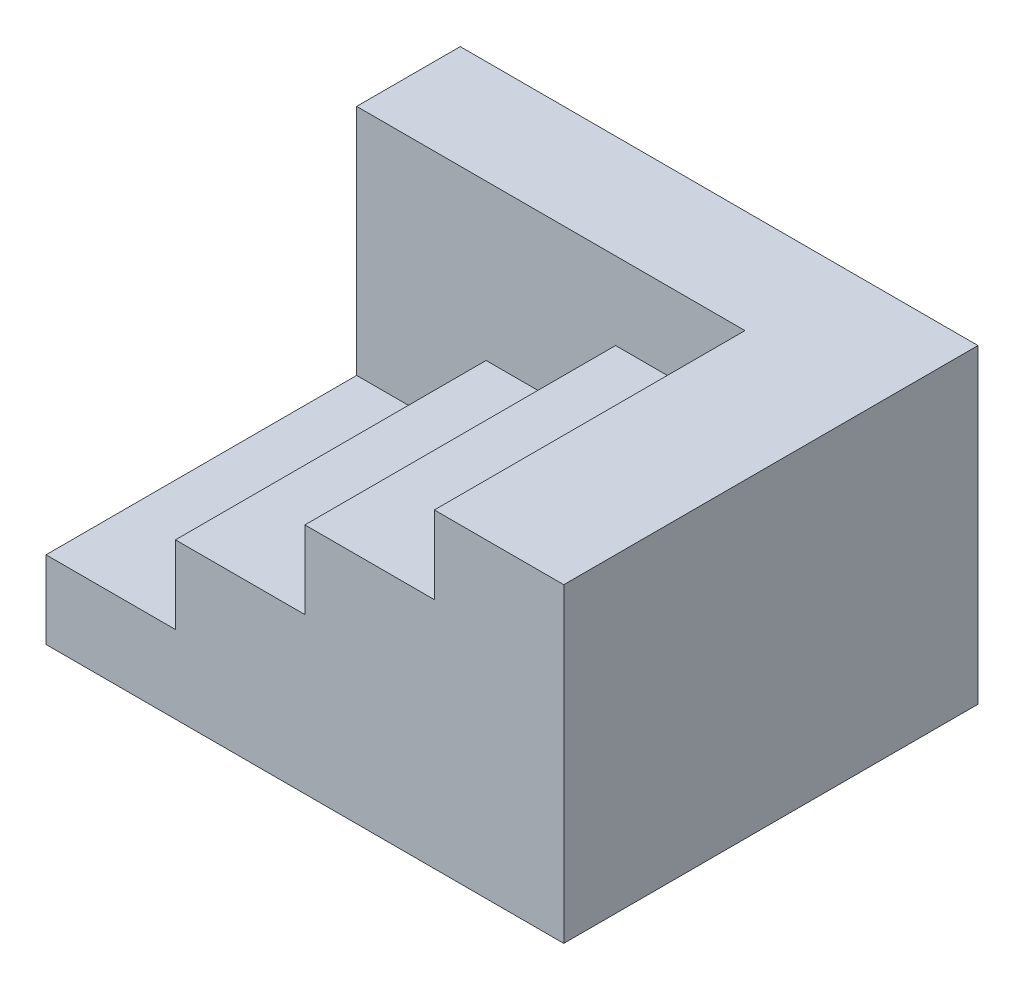
SolidWorks part; units mm, degrees
ref_plane "Front Plane" through (0, 0, 0) normal (0, 0, 1) x (1, 0, 0)
ref_plane "Top Plane" through (0, 0, 0) normal (0, 1, 0) x (1, 0, 0)
ref_plane "Right Plane" through (0, 0, 0) normal (1, 0, 0) x (0, 0, -1)
sketch "Sketch1" plane through (0, 0, 0) normal (0, 1, 0) x (1, 0, 0)
  line L1 (-50, -40) -> (50, -40)
  line L2 (-50, -40) -> (-50, 40)
  line L3 (-50, 40) -> (50, 40)
  line L4 (50, -40) -> (50, 40)
  point P0 (0, 0)
  dimension "D1" = 100
  dimension "D2" = 80
  dimension "D3" = 40
  dimension "D4" = 50
extrude "Boss-Extrude2" add sketch "Sketch1" along normal blind 60 contours L1 L4 L3 L2
sketch "Sketch3" plane through (0, 0, 40) normal (0, 0, 1) x (1, 0, 0)
  line L11 (50, 60) -> (25, 60)
  line L12 (25, 60) -> (25, 45)
  line L13 (25, 45) -> (0, 45)
  line L14 (0, 45) -> (0, 30)
  line L15 (-50, 0) -> (50, 0)
  line L16 (50, 0) -> (50, 60)
  line L17 (50, 60) -> (-50, 60)
  line L18 (-50, 60) -> (-50, 0)
  line L21 (50, 60) -> (-50, 60)
  line L23 (0, 30) -> (-25, 30)
  line L24 (-25, 30) -> (-25, 15)
  line L25 (-25, 15) -> (-50, 15)
  line L26 (-50, 60) -> (-50, 0) construction
  line L27 (-50, 15) -> (-50, 0)
  line L28 (-50, 0) -> (50, 0)
  line L29 (50, 0) -> (50, 60)
  line M10 (50, 60) -> (-50, 60)
  line M11 (-50, 60) -> (-50, 0)
  dimension "D1" = 25
  dimension "D2" = 15
  dimension "D3" = 25
  dimension "D4" = 15
  dimension "D5" = 25
  dimension "D6" = 15
  dimension "D7" = 0
sketch "Sketch4" plane through (0, 0, 40) normal (0, 0, 1) x (1, 0, 0)
extrude "Cut-Extrude3" cut sketch "Sketch3" against normal blind 60 contours L25 L24 L23 L14 L13 L12 M10 M11
